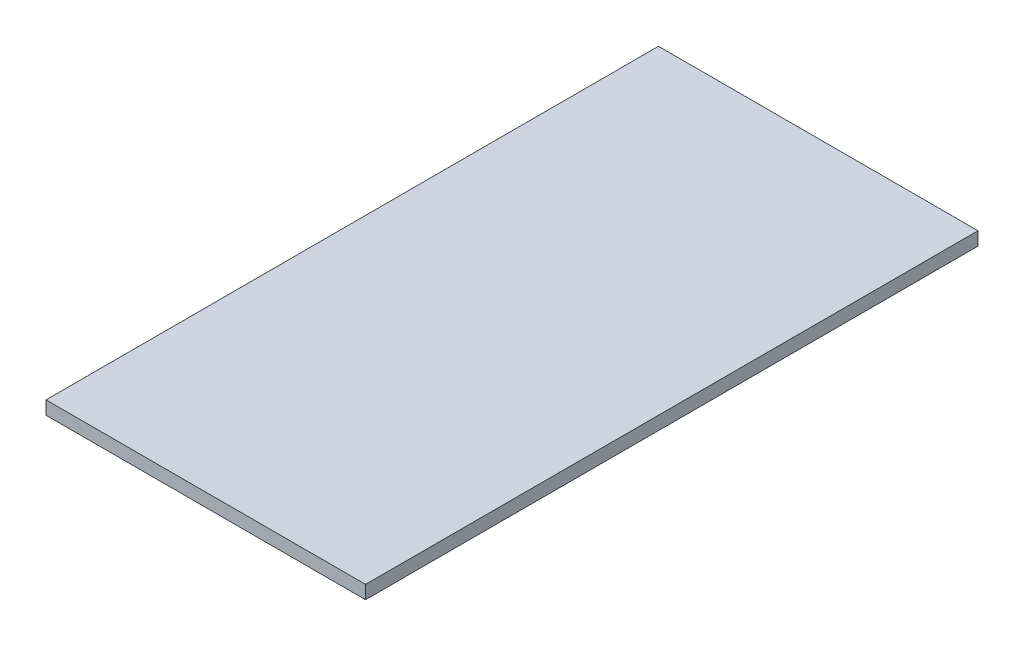
SolidWorks part; units mm, degrees
ref_plane "Front Plane" through (0, 0, 0) normal (0, 0, 1) x (1, 0, 0)
ref_plane "Top Plane" through (0, 0, 0) normal (0, 1, 0) x (1, 0, 0)
ref_plane "Right Plane" through (0, 0, 0) normal (1, 0, 0) x (0, 0, -1)
sketch "Sketch1" plane through (0, 0, 0) normal (0, 1, 0) x (1, 0, 0)
  line L1 (0, 0) -> (76.2, 0)
  line L2 (0, 0) -> (0, 146.05)
  line L3 (0, 146.05) -> (76.2, 146.05)
  line L4 (76.2, 0) -> (76.2, 146.05)
  dimension "D1" = 146.05
  dimension "D2" = 76.2
extrude "Boss-Extrude1" add sketch "Sketch1" along normal blind 3.175
